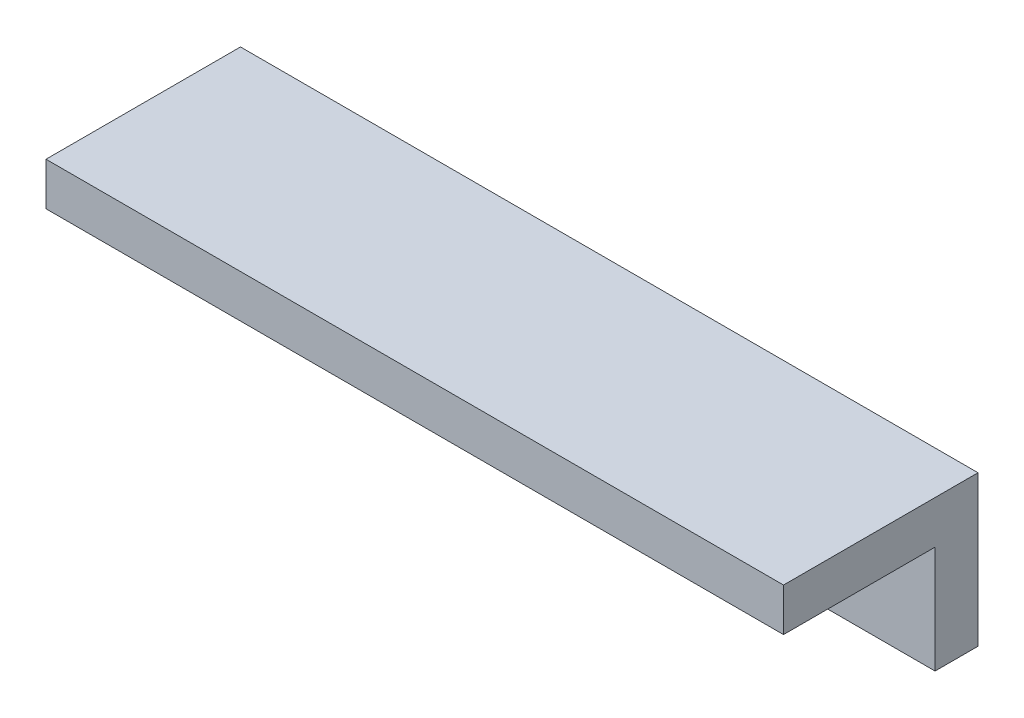
SolidWorks part; units mm, degrees
ref_plane "前视基准面" through (0, 0, 0) normal (0, 0, 1) x (1, 0, 0)
ref_plane "上视基准面" through (0, 0, 0) normal (0, 1, 0) x (1, 0, 0)
ref_plane "右视基准面" through (0, 0, 0) normal (1, 0, 0) x (0, 0, -1)
other "Configuration Table"
sketch "草图1" plane through (0, 0, 0) normal (0, 0, 1) x (1, 0, 0)
  line L1 (-29.2, -141.9) -> (29.2, -141.9)
  line L2 (-29.2, -141.9) -> (-29.2, -130)
  line L3 (-29.2, -130) -> (29.2, -130)
  line L4 (29.2, -141.9) -> (29.2, -130)
extrude "Female_mating_foot_VERIFY" add sketch "草图1" along normal blind 3.4 from offset 34.6
sketch "草图2" plane through (0, 0, 0) normal (0, 0, 1) x (1, 0, 0)
  line L1 (-29.2, -133.4) -> (29.2, -133.4)
  line L2 (-29.2, -133.4) -> (-29.2, -130)
  line L3 (-29.2, -130) -> (29.2, -130)
  line L4 (29.2, -133.4) -> (29.2, -130)
extrude "Right_angle_socket_INFERRED_NOT_CERTIFIED" add sketch "草图2" along normal blind 12 from offset 38
